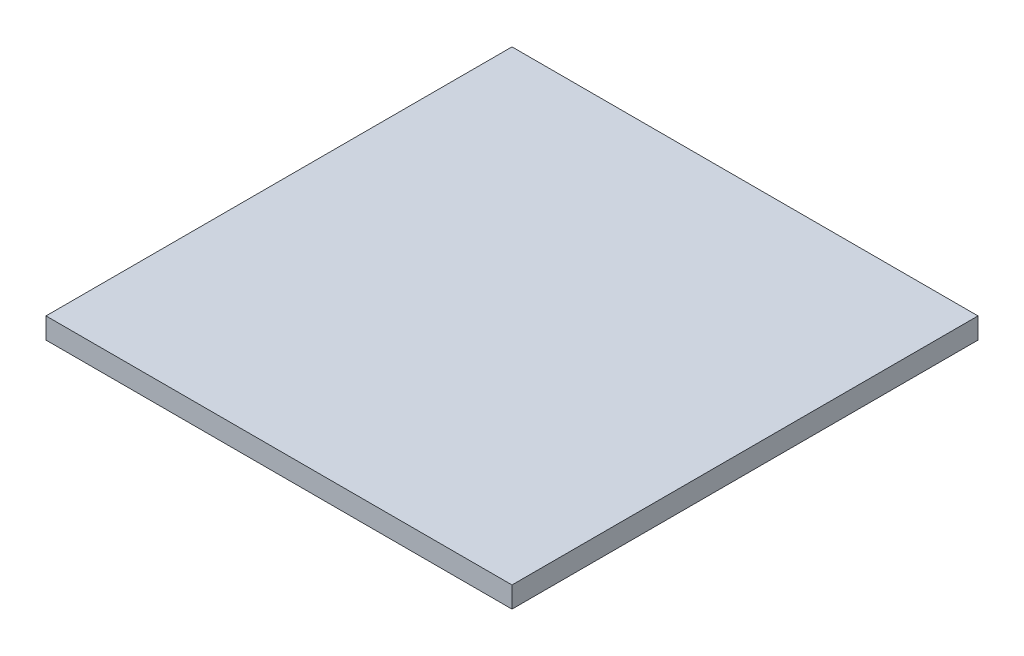
SolidWorks part; units mm, degrees
ref_plane "Front Plane" through (0, 0, 0) normal (0, 0, 1) x (1, 0, 0)
ref_plane "Top Plane" through (0, 0, 0) normal (0, 1, 0) x (1, 0, 0)
ref_plane "Right Plane" through (0, 0, 0) normal (1, 0, 0) x (0, 0, -1)
sketch "Esquisse1" plane through (0, 0, 0) normal (0, 1, 0) x (1, 0, 0)
  line L1 (-200, 200) -> (200, 200)
  line L2 (-200, 200) -> (-200, -200)
  line L3 (-200, -200) -> (200, -200)
  line L4 (200, 200) -> (200, -200)
  line L5 (-200, 200) -> (200, -200) construction
  line L6 (-200, -200) -> (200, 200) construction
  point P0 (0, 0)
extrude "Boss.-Extru.1" add sketch "Esquisse1" along normal blind 18
